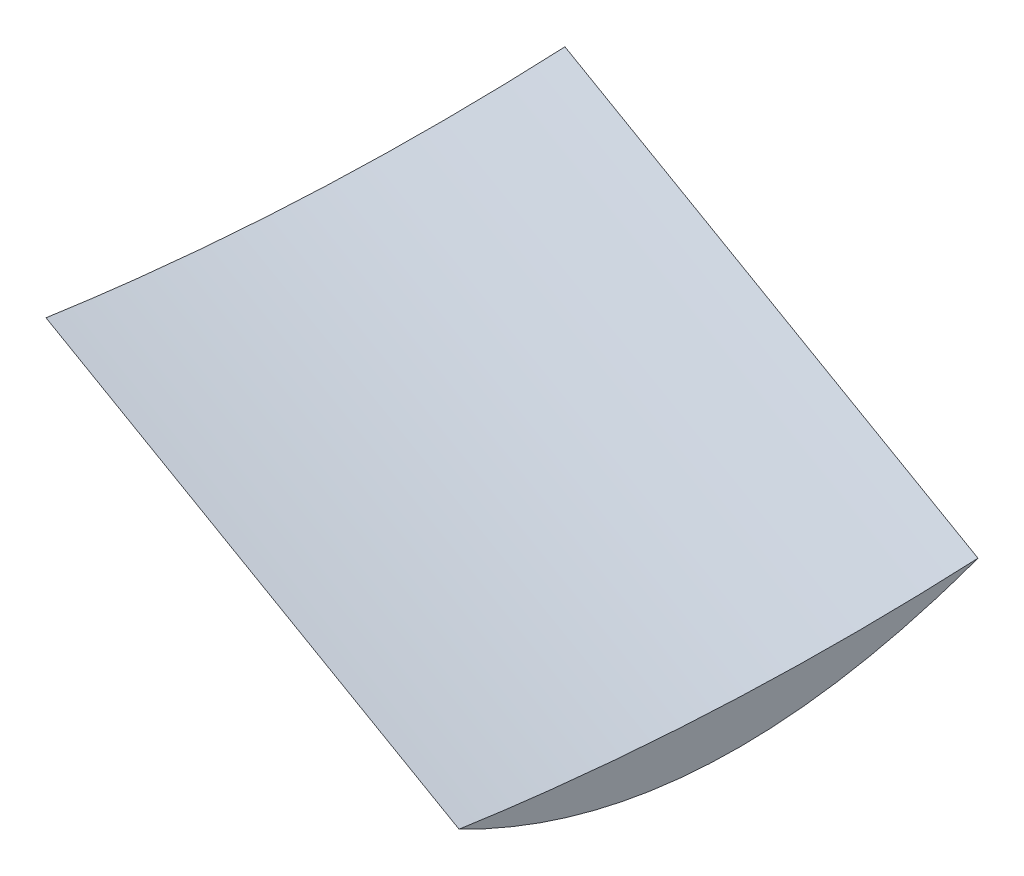
SolidWorks part; units mm, degrees
ref_plane "Front Plane" through (0, 0, 0) normal (0, 0, 1) x (1, 0, 0)
ref_plane "Top Plane" through (0, 0, 0) normal (0, 1, 0) x (1, 0, 0)
ref_plane "Right Plane" through (0, 0, 0) normal (1, 0, 0) x (0, 0, -1)
sketch "Sketch1" plane through (0, 0, 0) normal (1, 0, 0) x (0, 0, -1)
  spline S0 degree 2 poles (-44.9917, 21.7249) (207.2658, -14.7484) (462.4299, -2.5087) knots 0 0 0 1 1 1
  spline S1 degree 2 poles (-44.9917, 21.7249) (192.7329, -100.1016) (462.4299, -2.5087) knots 0 0 0 1 1 1
  point P0 (-44.9917, 21.7249)
  point P1 (462.4299, -2.5087)
  dimension "D2" = 50.8
  dimension "D1" = 508
sketch "Sketch2" plane through (0, 0, 0) normal (0, 1, 0) x (1, 0, 0)
  line L0 (0, -185.5968) -> (-635, 45.5243)
  line L1 (0, -44.9917) -> (0, 462.4299) construction
  line L2 (0, -185.5968) -> (0, -13.3335) construction
  dimension "D1" = 635
  dimension "D2" = 110
sweep "Sweep1" add profiles "Sketch1" path "Sketch2"
